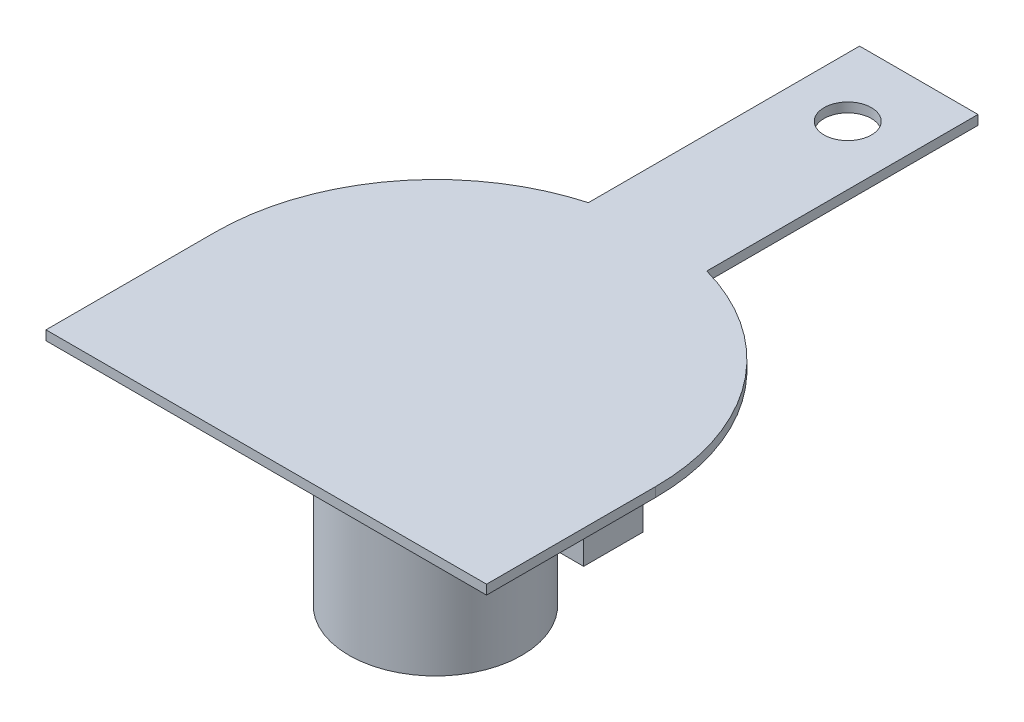
SolidWorks part; units mm, degrees
ref_plane "前视基准面" through (0, 0, 0) normal (0, 0, 1) x (1, 0, 0)
ref_plane "上视基准面" through (0, 0, 0) normal (0, 1, 0) x (1, 0, 0)
ref_plane "右视基准面" through (0, 0, 0) normal (1, 0, 0) x (0, 0, -1)
sketch "草图1" plane through (0, 0, 0) normal (0, 1, 0) x (1, 0, 0)
  line L0 (-2.5, 12.5288) -> (-2.5, 23.9788)
  line L2 (-9.3, 3.5712) -> (-9.3, -3.5712)
  line L3 (-9.3, -3.5712) -> (9.3, -3.5712)
  line L4 (9.3, 3.5712) -> (9.3, -3.5712)
  line L5 (-9.3, 3.5712) -> (9.3, -3.5712) construction
  line L6 (-9.3, -3.5712) -> (9.3, 3.5712) construction
  line L7 (-2.5, 23.9788) -> (2.5, 23.9788)
  line L8 (2.5, 23.9788) -> (2.5, 12.5288)
  line L9 (0, 3.5712) -> (0, 9.9211) construction
  line L10 (-9.3, 3.5712) -> (9.3, 3.5712) construction
  arc A0 (-9.3, 3.5712) -> (-2.5, 12.5288) centre (0, 3.5712) cw
  arc A1 (2.5, 12.5288) -> (9.3, 3.5712) centre (0, 3.5712) cw
  point P0 (0, 0)
  dimension "D1" = 18.6
  dimension "D2" = 16.1
  dimension "D3" = 5
  dimension "D4" = 27.55
extrude "凸台-拉伸1" add sketch "草图1" along normal blind 0.4
sketch "草图3" plane through (0, 0, 0) normal (0, -1, 0) x (1, 0, 0)
  line L0 (9.3, 3.5712) -> (9.3, -3.5712) construction
  line L1 (6.3, -1.0288) -> (8.8, -1.0288)
  line L2 (6.3, -1.0288) -> (6.3, -3.5288)
  line L3 (6.3, -3.5288) -> (8.8, -3.5288)
  line L4 (8.8, -1.0288) -> (8.8, -3.5288)
  line L5 (-9.3, 3.5712) -> (9.3, 3.5712) construction
  line L6 (0, 0) -> (0, -8.2426) construction
  line L7 (-8.8, -1.0288) -> (-8.8, -3.5288)
  line L8 (-6.3, -3.5288) -> (-8.8, -3.5288)
  line L9 (-6.3, -1.0288) -> (-6.3, -3.5288)
  line L10 (-6.3, -1.0288) -> (-8.8, -1.0288)
  dimension "D1" = 2.5
  dimension "D2" = 2.5
  dimension "D3" = 0.5
  dimension "D4" = 4.6
extrude "凸台-拉伸2" add sketch "草图3" along normal blind 1.5
sketch "草图5" plane through (0, 0, 0) normal (0, -1, 0) x (1, 0, 0)
  line L0 (2.5, -23.9788) -> (-2.5, -23.9788) construction
  circle A0 centre (0, -20.9788) radius 1
  dimension "D1" = 2
  dimension "D2" = 3
extrude "切除-拉伸1" cut sketch "草图5" against normal up to next
sketch "草图6" plane through (0, 0, 0) normal (0, -1, 0) x (1, 0, 0)
  line L0 (9.3, -3.5712) -> (-9.3, -3.5712) construction
  circle A0 centre (0, -3.5712) radius 3.65
  dimension "D1" = 7.3
extrude "凸台-拉伸3" add sketch "草图6" along normal blind 9 from surface at -0.4 starting at face at (0, 0.4, -21.9788)
